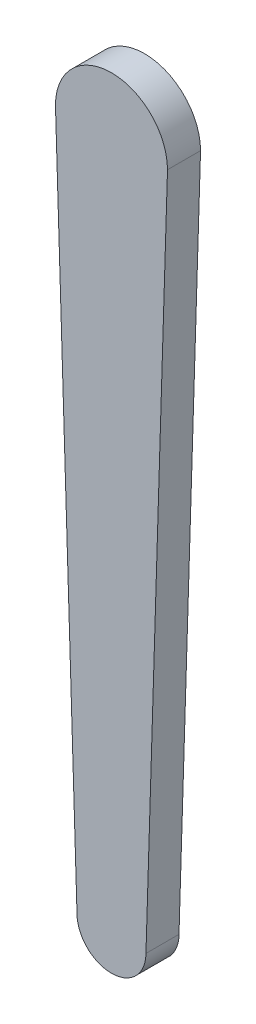
SolidWorks part; units mm, degrees
ref_plane "前视基准面" through (0, 0, 0) normal (0, 0, 1) x (1, 0, 0)
ref_plane "上视基准面" through (0, 0, 0) normal (0, 1, 0) x (1, 0, 0)
ref_plane "右视基准面" through (0, 0, 0) normal (1, 0, 0) x (0, 0, -1)
sketch "草图1" plane through (0, 0, 0) normal (0, 0, 1) x (1, 0, 0)
  line L0 (0, -120) -> (0, 120)
  line L1 (19.5, 120) -> (12, -120)
  line L2 (-19.5, 120) -> (-12, -120)
  circle A0 centre (0, 120) radius 19.5
  circle A1 centre (0, -120) radius 12
  point P4 (0, 0)
  dimension "D2" = 39
  dimension "D3" = 24
  dimension "D1" = 240
extrude "凸台-拉伸1" add sketch "草图1" along normal blind 11.5
